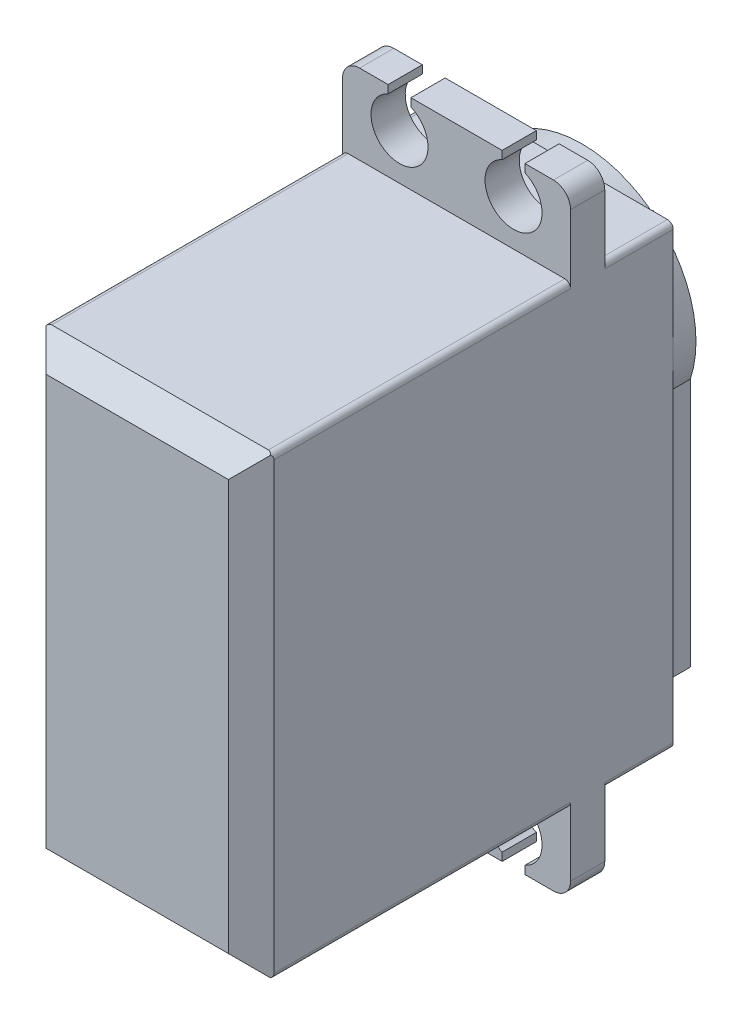
SolidWorks part; units mm, degrees
ref_plane "Plan de face" through (0, 0, 0) normal (0, 0, 1) x (1, 0, 0)
ref_plane "Plan de dessus" through (0, 0, 0) normal (0, 1, 0) x (1, 0, 0)
ref_plane "Plan de droite" through (0, 0, 0) normal (1, 0, 0) x (0, 0, -1)
sketch "Esquisse1" plane through (0, 0, 0) normal (1, 0, 0) x (0, 0, -1)
  line L0 (-26.2233, 0) -> (53.4917, 0) construction
  line L1 (0, -19.0499) -> (0, 25.7957) construction
  line L2 (0, -20) -> (0, 20)
  line L3 (0, 20) -> (28, 20)
  line L4 (28, 20) -> (28, 27)
  line L5 (28, 27) -> (31, 27)
  line L6 (31, 27) -> (31, 20)
  line L7 (31, 20) -> (37, 20)
  line L8 (37, 20) -> (37, -20)
  line L9 (31, -20) -> (37, -20)
  line L10 (31, -27) -> (31, -20)
  line L11 (28, -27) -> (31, -27)
  line L12 (28, -20) -> (28, -27)
  line L13 (0, -20) -> (28, -20)
  point P9 (33.6283, 0)
  point P15 (0, 0)
  point P16 (37, 0)
  dimension "D1" = 20
  dimension "D2" = 37
  dimension "D3" = 3
  dimension "D4" = 7
  dimension "D5" = 28
extrude "Boss.-Extru.1" add sketch "Esquisse1" along normal blind 20
sketch "Esquisse2" plane through (0, 0, -37) normal (0, 0, -1) x (-1, 0, 0)
  line L0 (-10, 20) -> (-10, -20) construction
  line L1 (0, 0) -> (-20, 0) construction
  line L2 (-20, -15) -> (0, -15) construction
  line L3 (-19.5, 6.8775) -> (-19.5, -15)
  line L4 (0, -20) -> (0, 20)
  line L5 (0, 20) -> (-20, 20)
  line L6 (-20, 20) -> (-20, -20)
  line L7 (-20, -20) -> (0, -20)
  line L8 (0, -20) -> (0, 20)
  line L9 (0, 20) -> (-20, 20)
  line L10 (-20, 20) -> (-20, -20)
  line L11 (-20, -20) -> (0, -20)
  line L12 (-19.5, -15) -> (-14.899, -15)
  line L13 (-0.5, 6.8775) -> (-0.5, -15)
  line L14 (-0.5, -15) -> (-5.101, -15)
  circle A0 centre (-10, 10) radius 10 construction
  circle A1 centre (-10, -10) radius 7 construction
  arc A2 (-14.899, -15) -> (-5.101, -15) centre (-10, -10) ccw
  arc A3 (-0.5, 6.8775) -> (-19.5, 6.8775) centre (-10, 10) ccw
  circle A4 centre (-10, -10) radius 10 construction
  dimension "D2" = 20
  dimension "D3" = 19
  dimension "D5" = 20
  dimension "D6" = 7
  dimension "D4" = 5
  dimension "D1" = 0
extrude "Boss.-Extru.2" add sketch "Esquisse2" along normal blind 2 contours A3 L3 L12 A2 L14 L13
sketch "Esquisse3" plane through (0, 0, -39) normal (0, 0, -1) x (-1, 0, 0)
  line L4 (-19.5, 6.8775) -> (-19.5, -15)
  line L5 (-19.5, -15) -> (-14.899, -15)
  line L6 (-5.101, -15) -> (-0.5, -15)
  line L7 (-0.5, -15) -> (-0.5, 6.8775)
  line L8 (-19.5, 6.8775) -> (-19.5, -15)
  line L9 (-19.5, -15) -> (-14.899, -15)
  line L10 (-5.101, -15) -> (-0.5, -15)
  line L11 (-0.5, -15) -> (-0.5, 6.8775)
  circle A0 centre (-10, 10) radius 6.5
  arc A2 (-0.5, 6.8775) -> (-19.5, 6.8775) centre (-10, 10) ccw
  arc A3 (-14.899, -15) -> (-5.101, -15) centre (-10, -10) ccw
  arc A4 (-0.5, 6.8775) -> (-19.5, 6.8775) centre (-10, 10) ccw
  arc A5 (-14.899, -15) -> (-5.101, -15) centre (-10, -10) ccw
  dimension "D2" = 13
  dimension "D1" = 0
extrude "Boss.-Extru.3" add sketch "Esquisse3" along normal blind 1 contours A0
sketch "Esquisse4" plane through (0, 0, -40) normal (0, 0, -1) x (-1, 0, 0)
  circle A0 centre (-10, 10) radius 5.5
  circle A1 centre (-10, 10) radius 6.5
  circle A2 centre (-10, 10) radius 6.5
  dimension "D2" = 11
  dimension "D1" = 0
extrude "Boss.-Extru.4" add sketch "Esquisse4" along normal blind 0.25 contours A0
sketch "Esquisse5" plane through (0, 0, -40.25) normal (0, 0, -1) x (-1, 0, 0)
  circle A0 centre (-10, 10) radius 3
  circle A1 centre (-10, 10) radius 5.5
  circle A2 centre (-10, 10) radius 5.5
  dimension "D2" = 6
  dimension "D1" = 0
extrude "Boss.-Extru.5" add sketch "Esquisse5" along normal blind 4 contours A0
sketch "Esquisse6" plane through (0, 0, -44.25) normal (0, 0, -1) x (-1, 0, 0)
  line L0 (-10, 10) -> (-10, 13.8022) construction
  line L1 (-10, 10) -> (-10.7054, 14.0007) construction
  line L2 (-10, 13) -> (-10.4341, 12.462)
  line L3 (-10, 13) -> (-9.5659, 12.462)
  line L4 (-8.9739, 12.8191) -> (-9.5659, 12.462)
  line L5 (-8.9739, 12.8191) -> (-8.75, 12.1651)
  line L6 (-8.0716, 12.2981) -> (-8.75, 12.1651)
  line L7 (-8.0716, 12.2981) -> (-8.0849, 11.607)
  line L8 (-7.4019, 11.5) -> (-8.0849, 11.607)
  line L9 (-7.4019, 11.5) -> (-7.6508, 10.8551)
  line L10 (-7.0456, 10.5209) -> (-7.6508, 10.8551)
  line L11 (-7.0456, 10.5209) -> (-7.5, 10)
  line L12 (-7.0456, 9.4791) -> (-7.5, 10)
  line L13 (-7.0456, 9.4791) -> (-7.6508, 9.1449)
  line L14 (-7.4019, 8.5) -> (-7.6508, 9.1449)
  line L15 (-7.4019, 8.5) -> (-8.0849, 8.393)
  line L16 (-8.0716, 7.7019) -> (-8.0849, 8.393)
  line L17 (-8.0716, 7.7019) -> (-8.75, 7.8349)
  line L18 (-8.9739, 7.1809) -> (-8.75, 7.8349)
  line L19 (-8.9739, 7.1809) -> (-9.5659, 7.538)
  line L20 (-10, 7) -> (-9.5659, 7.538)
  line L21 (-10, 7) -> (-10.4341, 7.538)
  line L22 (-11.0261, 7.1809) -> (-10.4341, 7.538)
  line L23 (-11.0261, 7.1809) -> (-11.25, 7.8349)
  line L24 (-11.9284, 7.7019) -> (-11.25, 7.8349)
  line L25 (-11.9284, 7.7019) -> (-11.9151, 8.393)
  line L26 (-12.5981, 8.5) -> (-11.9151, 8.393)
  line L27 (-12.5981, 8.5) -> (-12.3492, 9.1449)
  line L28 (-12.9544, 9.4791) -> (-12.3492, 9.1449)
  line L29 (-12.9544, 9.4791) -> (-12.5, 10)
  line L30 (-12.9544, 10.5209) -> (-12.5, 10)
  line L31 (-12.9544, 10.5209) -> (-12.3492, 10.8551)
  line L32 (-12.5981, 11.5) -> (-12.3492, 10.8551)
  line L33 (-12.5981, 11.5) -> (-11.9151, 11.607)
  line L34 (-11.9284, 12.2981) -> (-11.9151, 11.607)
  line L35 (-11.9284, 12.2981) -> (-11.25, 12.1651)
  line L36 (-11.0261, 12.8191) -> (-11.25, 12.1651)
  line L37 (-11.0261, 12.8191) -> (-10.4341, 12.462)
  circle A0 centre (-10, 10) radius 2.5 construction
  circle A1 centre (-10, 10) radius 3
  circle A2 centre (-10, 10) radius 3
  point P63 (-10, 10)
  circle M5 centre (-10, 10) radius 3
  dimension "D3" = 5
  dimension "D2" = 10
  dimension "D1" = 0
  dimension "D4" = 18
extrude "Enlèv. mat.-Extru.1" cut sketch "Esquisse6" against normal blind 4 contours L4 L3 M5 | L37 L2 M5 | L36 L35 M5 | L34 L33 M5 | L32 L31 M5 | L30 L29 M5 | L28 L27 M5 | L26 L25 M5 | L24 L23 M5 | L22 L21 M5 | L20 L19 M5 | L18 L17 M5 | L16 L15 M5 | L14 L13 M5 | L12 L11 M5 | L10 L9 M5 | L8 L7 M5 | L6 L5 M5 | A2
sketch "Esquisse7" plane through (0, 0, -31) normal (0, 0, -1) x (-1, 0, 0)
  line L0 (-20, 24) -> (0, 24) construction
  line L1 (0, 0) -> (-32.0049, 0) construction
  line L2 (-10, 27) -> (-10, -29.4324) construction
  line L3 (-6, 27) -> (-6, 26.2913)
  line L4 (0, 20) -> (0, 27)
  line L5 (0, 27) -> (-20, 27)
  line L6 (-20, 27) -> (-20, 20)
  line L7 (-20, 20) -> (0, 20)
  line L8 (0, 20) -> (0, 27)
  line L9 (0, 27) -> (-20, 27)
  line L10 (-20, 27) -> (-20, 20)
  line L11 (-20, 20) -> (0, 20)
  line L12 (0, -27) -> (0, -20)
  line L13 (0, -20) -> (-20, -20)
  line L14 (-20, -20) -> (-20, -27)
  line L15 (-20, -27) -> (0, -27)
  line L16 (0, -27) -> (0, -20)
  line L17 (0, -20) -> (-20, -20)
  line L18 (-20, -20) -> (-20, -27)
  line L19 (-20, -27) -> (0, -27)
  line L20 (-4, 27) -> (-4, 26.2913)
  line L21 (-6, 27) -> (-4, 27)
  line L22 (-16, 27) -> (-16, 26.2913)
  line L23 (-14, 27) -> (-16, 27)
  line L24 (-14, 27) -> (-14, 26.2913)
  line L25 (-14, -27) -> (-16, -27)
  line L26 (-14, -27) -> (-14, -26.2913)
  line L27 (-16, -27) -> (-16, -26.2913)
  line L28 (-4, -27) -> (-4, -26.2913)
  line L29 (-6, -27) -> (-4, -27)
  line L30 (-6, -27) -> (-6, -26.2913)
  circle A0 centre (-5, 24) radius 2.5 construction
  arc A1 (-6, 26.2913) -> (-4, 26.2913) centre (-5, 24) ccw
  arc A2 (-14, 26.2913) -> (-16, 26.2913) centre (-15, 24) cw
  arc A3 (-14, -26.2913) -> (-16, -26.2913) centre (-15, -24) ccw
  arc A4 (-6, -26.2913) -> (-4, -26.2913) centre (-5, -24) cw
  dimension "D3" = 5
  dimension "D4" = 4
  dimension "D5" = 5
  dimension "D6" = 2
  dimension "D1" = 0
  dimension "D2" = 0
extrude "Enlèv. mat.-Extru.2" cut sketch "Esquisse7" against normal through all contours L3 A1 L20 L9 | A2 L24 L9 L22 | A4 L30 L19 L28 | L26 A3 L27 L19
fillet "Congé1" radius 1.5 4 edges at (20, 27, -29.5) (20, -27, -29.5) (0, -27, -29.5) (0, 27, -29.5)
chamfer "Chanfrein1" distance 2 angle 45 4 edges at (10, 20, 0) (20, 0, 0) (10, -20, 0) (0, 0, 0)
fillet "Congé2" radius 0.5 8 edges at (20, -20, -34) (20, -20, -15) (0, -20, -34) (0, -20, -15) (0, 20, -34) (0, 20, -15) (20, 20, -34) (20, 20, -15)
